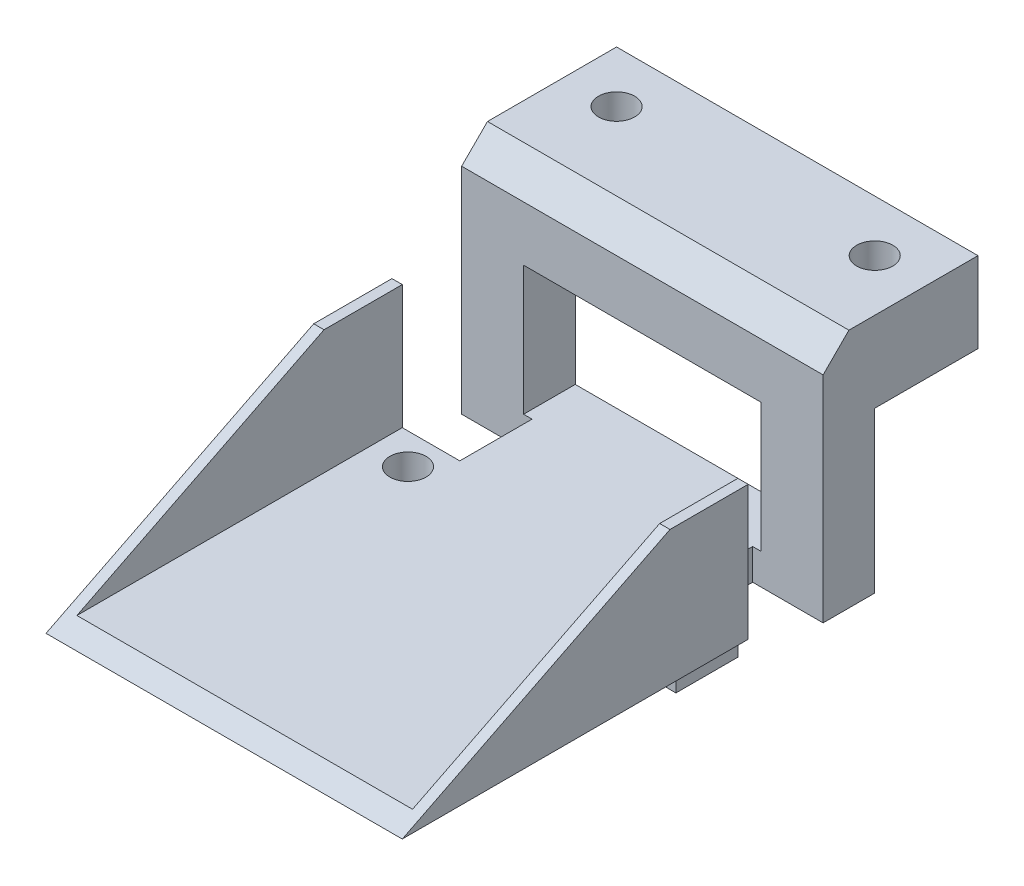
SolidWorks part; units mm, degrees
ref_plane "Front Plane" through (0, 0, 0) normal (0, 0, 1) x (1, 0, 0)
ref_plane "Top Plane" through (0, 0, 0) normal (0, 1, 0) x (1, 0, 0)
ref_plane "Right Plane" through (0, 0, 0) normal (1, 0, 0) x (0, 0, -1)
sketch "Sketch1" plane through (0, 0, 0) normal (0, 1, 0) x (1, 0, 0)
  line L0 (0, 0) -> (0, 5.0675) construction
  line L1 (-16.25, 3) -> (16.25, 3)
  line L2 (-16.25, 3) -> (-16.25, -3)
  line L3 (-16.25, -3) -> (16.25, -3)
  line L4 (16.25, 3) -> (16.25, -3)
  line L5 (-16.25, 3) -> (16.25, -3) construction
  line L6 (-16.25, -3) -> (16.25, 3) construction
  circle A0 centre (-12.7, 0) radius 1.75
  circle A1 centre (12.7, 0) radius 1.75
  point P0 (0, 0)
  point P12 (0, 0)
  dimension "D3" = 3.5
  dimension "D4" = 25.4
  dimension "D1" = 6
  dimension "D2" = 32.5
extrude "Boss-Extrude1" add sketch "Sketch1" along normal blind 3
sketch "Sketch2" plane through (0, 0, 0) normal (0, -1, 0) x (1, 0, 0)
  line L0 (16.25, -3) -> (-16.25, -3) construction
  line L1 (-10.68, -3) -> (10.68, -3)
  line L2 (-10.68, -3) -> (-10.68, -15)
  line L3 (-10.68, -15) -> (10.68, -15)
  line L4 (10.68, -3) -> (10.68, -15)
  line L5 (0, -3) -> (0, -7.9957) construction
  point P8 (0, 0)
  point P9 (0, 0)
  dimension "D1" = 21.36
  dimension "D2" = 12
extrude "Boss-Extrude2" add sketch "Sketch2" against normal up to surface (3 mm away) up to face at (-12.7, 3, 1.75)
sketch "Sketch3" plane through (0, 0, 0) normal (0, -1, 0) x (1, 0, 0)
  line L0 (-10.68, -15) -> (10.68, -15) construction
  line L1 (-17.5, -10) -> (17.5, -10)
  line L2 (-17.5, -10) -> (-17.5, -15)
  line L3 (-17.5, -15) -> (17.5, -15)
  line L4 (17.5, -10) -> (17.5, -15)
  line L5 (-17.5, -10) -> (17.5, -15) construction
  line L6 (-17.5, -15) -> (17.5, -10) construction
  point P0 (0, -12.5)
  point P5 (0, 0)
  dimension "D1" = 35
  dimension "D2" = 5
extrude "Boss-Extrude3" add sketch "Sketch3" against normal up to surface (3 mm away) up to face at (-12.7, 3, 1.75)
sketch "Sketch4" plane through (0, 3, 0) normal (0, 1, 0) x (1, 0, 0)
  line L0 (-17.5, 15) -> (17.5, 15) construction
  line L1 (-17.5, 10) -> (-11.5, 10)
  line L2 (-17.5, 10) -> (-17.5, 15)
  line L3 (-17.5, 15) -> (-11.5, 15)
  line L4 (-11.5, 10) -> (-11.5, 15)
  line L5 (0, 0) -> (0, 6.0638) construction
  line L6 (17.5, 15) -> (11.5, 15)
  line L7 (11.5, 10) -> (11.5, 15)
  line L8 (17.5, 10) -> (11.5, 10)
  line L9 (17.5, 10) -> (17.5, 15)
  dimension "D1" = 23
extrude "Boss-Extrude4" add sketch "Sketch4" along normal blind 12.5
sketch "Sketch5" plane through (0, 15.5, 0) normal (0, 1, 0) x (1, 0, 0)
  line L1 (17.5, 10) -> (-17.5, 10)
  line L2 (17.5, 10) -> (17.5, 25)
  line L3 (17.5, 25) -> (-17.5, 25)
  line L4 (-17.5, 10) -> (-17.5, 25)
  point P4 (0, 0)
  point P5 (-15.8455, 19.841)
  point P6 (-17.5, 10)
  dimension "D1" = 15
extrude "Boss-Extrude5" add sketch "Sketch5" along normal blind 7.8
chamfer "Chamfer1" distance 2.5 angle 45 1 edges at (0, 23.3, -10)
sketch "Sketch6" plane through (0, 15.5, 0) normal (0, -1, 0) x (1, 0, 0)
  line L0 (-17.5, -20) -> (17.5, -20) construction
  line L1 (-17.5, -25) -> (-17.5, -15) construction
  line L2 (17.5, -15) -> (17.5, -25) construction
  line L3 (0, -20) -> (0, -22.6622) construction
  circle A0 centre (-12.5, -20) radius 1.75
  circle A1 centre (12.5, -20) radius 1.75
  dimension "D1" = 3.5
  dimension "D2" = 25
extrude "Cut-Extrude1" cut sketch "Sketch6" against normal through all
sketch "Sketch7" plane through (-16.25, 0, 0) normal (-1, 0, 0) x (0, 0, 1)
  line L0 (-3, 2) -> (-3, 18.8)
  line L1 (-3, 18.8) -> (30.5, 2)
  line L2 (30.5, 2) -> (-3, 2)
  line L3 (-3, 3) -> (-3, 0) construction
  line L4 (-3, 3) -> (-10, 3) construction
  point P4 (0, 0)
  point P5 (-3, 2.2423)
  dimension "D1" = 16.8
  dimension "D2" = 33.5
  dimension "D3" = 1
extrude "Boss-Extrude6" add sketch "Sketch7" along normal blind 1
mirror "Mirror1" about plane through (0, 0, 0) normal (1, 0, 0) of "Boss-Extrude6"
sketch "Sketch8" plane through (0, 0, 3) normal (0, 0, 1) x (1, 0, 0)
  line L1 (-16.25, 2) -> (16.25, 2)
  line L2 (-16.25, 2) -> (-16.25, 3)
  line L3 (-16.25, 3) -> (16.25, 3)
  line L4 (16.25, 2) -> (16.25, 3)
extrude "Boss-Extrude7" add sketch "Sketch8" along normal up to vertex (27.5 mm away) up to point (-16.25, 2, 30.5)
sketch "Sketch9" plane through (16.25, 0, 0) normal (1, 0, 0) x (0, 0, -1)
  line L3 (-30.5, 2) -> (-28.506, 3)
  line L4 (-28.506, 3) -> (-30.5, 3)
  line L5 (-30.5, 3) -> (-30.5, 2)
  line L6 (-30.5, 2) -> (-28.506, 3)
  line L7 (-28.506, 3) -> (-30.5, 3)
  line L8 (-30.5, 3) -> (-30.5, 2)
  dimension "D1" = 0
extrude "Cut-Extrude2" cut sketch "Sketch9" against normal up to surface (33.5 mm away) up to face at (-17.25, 7.6, 8.1667)
sketch "Sketch10" plane through (-17.25, 0, 0) normal (-1, 0, 0) x (0, 0, 1)
  line L0 (-3, 15) -> (4.5774, 15)
  line L1 (-3, 18.8) -> (-3, 2) construction
  line L2 (30.5, 2) -> (-3, 18.8) construction
  line L6 (-3, 2) -> (30.5, 2)
  line L7 (30.5, 2) -> (-3, 18.8)
  line L8 (-3, 18.8) -> (-3, 2)
  line L10 (4.5774, 15) -> (-3, 18.8)
  line L11 (-3, 18.8) -> (-3, 15)
  dimension "D1" = 0
  dimension "D2" = 3.8
extrude "Cut-Extrude3" cut sketch "Sketch10" against normal through all
